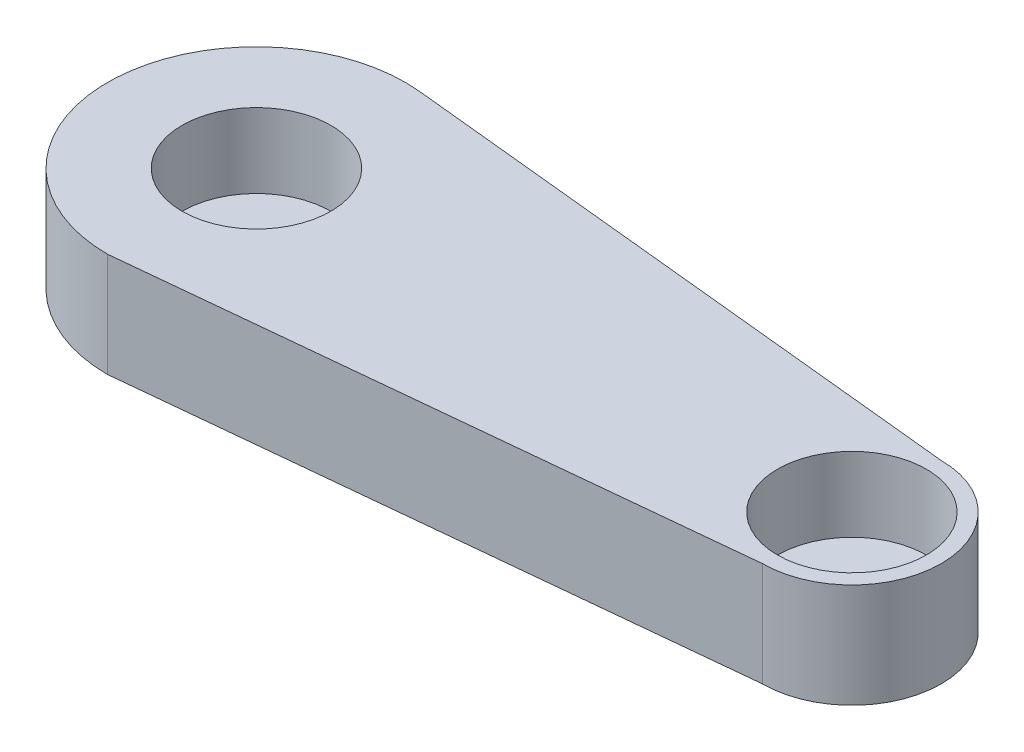
SolidWorks part; units mm, degrees
ref_plane "Front Plane" through (0, 0, 0) normal (0, 0, 1) x (1, 0, 0)
ref_plane "Top Plane" through (0, 0, 0) normal (0, 1, 0) x (1, 0, 0)
ref_plane "Right Plane" through (0, 0, 0) normal (1, 0, 0) x (0, 0, -1)
sketch "Sketch2" plane through (0, 0, 0) normal (0, 1, 0) x (1, 0, 0)
  line L1 (-94.9043, 99.491) -> (295.0194, 60)
  line L2 (-104.9806, -100) -> (295.0194, -60)
  arc A0 (-94.9043, 99.491) -> (-85.1786, -98.0198) centre (-104.9806, 0) ccw
  arc A1 (295.0194, -60) -> (295.0194, 60) centre (295.0194, 0) ccw
  dimension "D1" = 200
  dimension "D3" = 120
  dimension "D2" = 400
extrude "Boss-Extrude1" add sketch "Sketch2" along normal blind 70 contours L2 A1 L1 A0
sketch "Sketch3" plane through (0, 70, 0) normal (0, 1, 0) x (1, 0, 0)
  circle A0 centre (-104.9806, 0) radius 50
  circle A1 centre (295.0194, 0) radius 50
  dimension "D1" = 100
  dimension "D2" = 100
extrude "Cut-Extrude1" cut sketch "Sketch3" against normal blind 50
